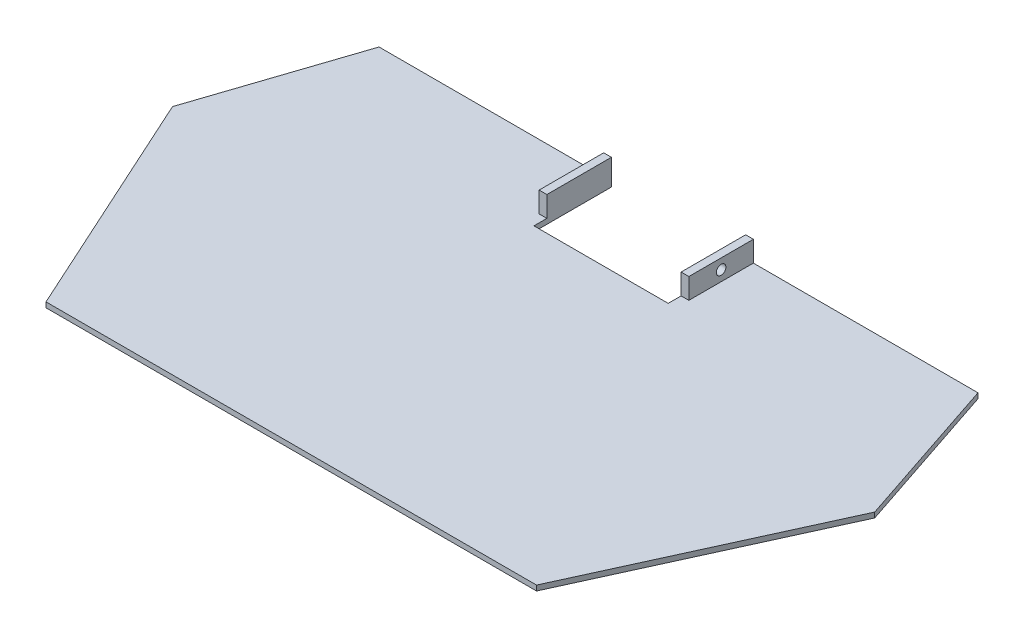
SolidWorks part; units mm, degrees
ref_plane "前视基准面" through (0, 0, 0) normal (0, 0, 1) x (1, 0, 0)
ref_plane "上视基准面" through (0, 0, 0) normal (0, 1, 0) x (1, 0, 0)
ref_plane "右视基准面" through (0, 0, 0) normal (1, 0, 0) x (0, 0, -1)
other "Configuration Table"
sketch "草图1" plane through (0, 0, 0) normal (0, 1, 0) x (1, 0, 0)
  line L0 (0, 57.6481) -> (0, -101.8228) construction
  line L1 (26, 30) -> (-26, 30)
  line L2 (-26, 30) -> (-26, 60)
  line L3 (-26, 60) -> (-116, 60)
  line L4 (-116, 60) -> (-136, 0)
  line L5 (-136, 0) -> (-95, -90)
  line L6 (-95, -90) -> (95, -90)
  line L7 (136, 0) -> (95, -90)
  line L8 (116, 60) -> (136, 0)
  line L9 (26, 60) -> (116, 60)
  line L10 (26, 30) -> (26, 60)
  point P12 (0, -90)
  point P13 (0, 30)
  dimension "D1" = 26
  dimension "D2" = 90
  dimension "D3" = 150
  dimension "D4" = 60
  dimension "D5" = 30
  dimension "D6" = 30
  dimension "D7" = 190
  dimension "D8" = 20
extrude "凸台-拉伸1" add sketch "草图1" along normal blind 2
sketch "草图2" plane through (0, 2, 0) normal (0, 1, 0) x (1, 0, 0)
  line L0 (0, 53.9156) -> (0, 0) construction
  line L1 (29, 60) -> (29, 35)
  line L2 (-26, 60) -> (-29, 60)
  line L3 (-26, 60) -> (-26, 35)
  line L4 (-26, 35) -> (-29, 35)
  line L5 (-29, 60) -> (-29, 35)
  line L6 (26, 35) -> (29, 35)
  line L7 (26, 60) -> (26, 35)
  line L8 (26, 60) -> (29, 60)
  dimension "D1" = 3
  dimension "D2" = 25
extrude "凸台-拉伸2" add sketch "草图2" along normal blind 8
sketch "草图3" plane through (26, 0, 0) normal (-1, 0, 0) x (0, 0, 1)
  line L0 (-47.5, 10) -> (-47.5, 2.577) construction
  line L1 (-60, 10) -> (-35, 10) construction
  circle A0 centre (-47.5, 6) radius 1.85
  dimension "D1" = 3.7
  dimension "D2" = 4
extrude "切除-拉伸1" cut sketch "草图3" against normal blind 8
